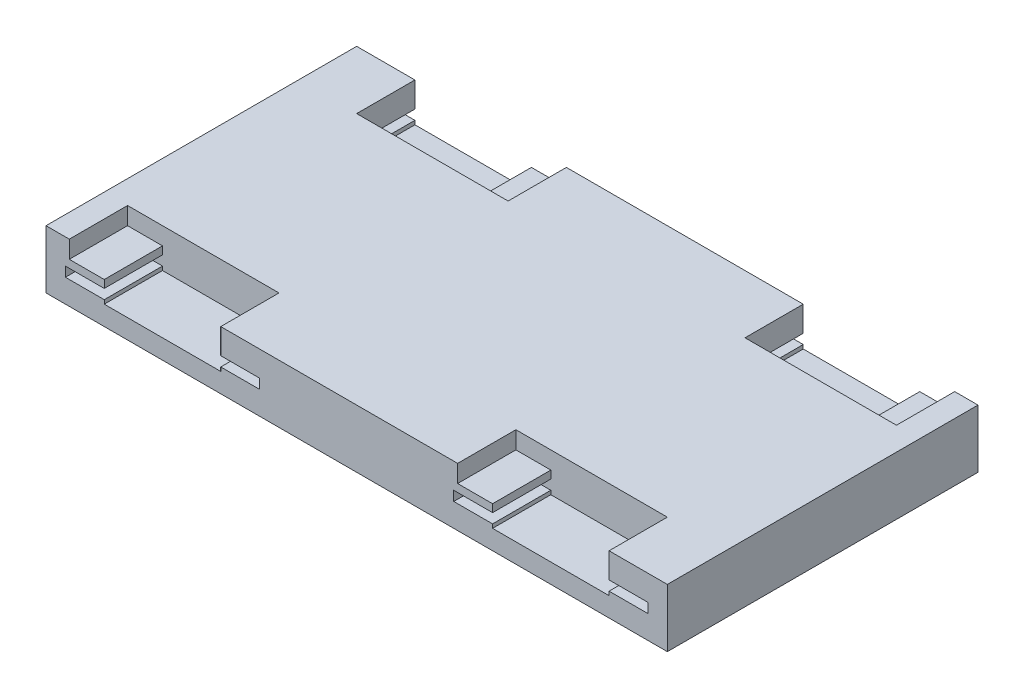
SolidWorks part; units mm, degrees
ref_plane "Front Plane" through (0, 0, 0) normal (0, 0, 1) x (1, 0, 0)
ref_plane "Top Plane" through (0, 0, 0) normal (0, 1, 0) x (1, 0, 0)
ref_plane "Right Plane" through (0, 0, 0) normal (1, 0, 0) x (0, 0, -1)
sketch "Sketch1" plane through (0, 0, 0) normal (0, 1, 0) x (1, 0, 0)
  line L1 (-160, 80) -> (160, 80)
  line L2 (-160, 80) -> (-160, -80)
  line L3 (-160, -80) -> (160, -80)
  line L4 (160, 80) -> (160, -80)
  line L5 (-160, 80) -> (160, -80) construction
  line L6 (-160, -80) -> (160, 80) construction
  point P0 (0, 0)
  dimension "D1" = 320
  dimension "D2" = 160
extrude "Boss-Extrude1" add sketch "Sketch1" along normal blind 20
sketch "Sketch2" plane through (0, 20, 0) normal (0, 1, 0) x (1, 0, 0)
  line L0 (-160, -80) -> (160, -80) construction
  line L1 (-130, -80) -> (-70, -80)
  line L2 (-130, -80) -> (-130, -50)
  line L3 (-130, -50) -> (-70, -50)
  line L4 (-70, -80) -> (-70, -50)
  line L5 (-160, 80) -> (-160, -80) construction
  dimension "D1" = 60
  dimension "D2" = 30
  dimension "D3" = 30
extrude "Cut-Extrude1" cut sketch "Sketch2" against normal blind 28
sketch "Sketch3" plane through (0, 0, 80) normal (0, 0, 1) x (1, 0, 0)
  line L0 (-130, 0) -> (-130, 20) construction
  line L1 (-130, 7) -> (-150, 7)
  line L2 (-130, 7) -> (-130, 2)
  line L3 (-130, 2) -> (-150, 2)
  line L4 (-150, 7) -> (-150, 2)
  line L5 (-160, 0) -> (-130, 0) construction
  line L6 (-70, 0) -> (-70, 20) construction
  line L7 (-70, 7) -> (-50, 7)
  line L8 (-70, 7) -> (-70, 2)
  line L9 (-70, 2) -> (-50, 2)
  line L10 (-50, 7) -> (-50, 2)
  line L11 (88, 0) -> (-88, 0) construction
  dimension "D1" = 2
  dimension "D2" = 5
  dimension "D3" = 20
  dimension "D4" = 20
  dimension "D5" = 5
  dimension "D6" = 2
extrude "Cut-Extrude3" cut sketch "Sketch3" against normal blind 30
mirror "Mirror2" about plane through (0, 0, 0) normal (1, 0, 0) of "Cut-Extrude1", "Cut-Extrude3"
mirror "Mirror3" about plane through (0, 0, 0) normal (0, 0, 1) of "Mirror2", "Cut-Extrude1", "Cut-Extrude3"
sketch "Sketch5" plane through (0, 0, 80) normal (0, 0, 1) x (1, 0, 0)
  line L0 (-130, 7) -> (-130, 20) construction
  line L1 (-130, 11) -> (-148, 11)
  line L2 (-130, 11) -> (-130, 20)
  line L3 (-130, 20) -> (-148, 20)
  line L4 (-148, 11) -> (-148, 20)
  line L5 (-160, 20) -> (-130, 20) construction
  line L6 (-130, 7) -> (-150, 7) construction
  dimension "D1" = 4
  dimension "D2" = 18
extrude "Cut-Extrude4" cut sketch "Sketch5" against normal blind 30
sketch "Sketch6" plane through (0, 0, 80) normal (0, 0, 1) x (1, 0, 0)
  line L0 (70, 7) -> (70, 20) construction
  line L1 (70, 11) -> (52, 11)
  line L2 (70, 11) -> (70, 20)
  line L3 (70, 20) -> (52, 20)
  line L4 (52, 11) -> (52, 20)
  line L5 (50, 7) -> (70, 7) construction
  dimension "D1" = 18
  dimension "D2" = 4
extrude "Cut-Extrude5" cut sketch "Sketch6" against normal blind 30
sketch "Sketch8" plane through (0, 0, -80) normal (0, 0, -1) x (-1, 0, 0)
  line L0 (-130, 7) -> (-130, 20) construction
  line L1 (-130, 11) -> (-148, 11)
  line L2 (-130, 11) -> (-130, 20)
  line L3 (-130, 20) -> (-148, 20)
  line L4 (-148, 11) -> (-148, 20)
  line L5 (-160, 20) -> (-130, 20) construction
  line L6 (-130, 7) -> (-150, 7) construction
  dimension "D1" = 18
  dimension "D2" = 4
extrude "Cut-Extrude6" cut sketch "Sketch8" against normal blind 30
sketch "Sketch9" plane through (0, 0, -80) normal (0, 0, -1) x (-1, 0, 0)
  line L0 (70, 20) -> (70, 7) construction
  line L1 (70, 11) -> (52, 11)
  line L2 (70, 11) -> (70, 20)
  line L3 (70, 20) -> (52, 20)
  line L4 (52, 11) -> (52, 20)
  line L5 (-70, 20) -> (70, 20) construction
  line L6 (50, 7) -> (70, 7) construction
  dimension "D1" = 18
  dimension "D2" = 4
extrude "Cut-Extrude7" cut sketch "Sketch9" against normal blind 30
sketch "Sketch10" plane through (0, 0, 0) normal (0, -1, 0) x (1, 0, 0)
  line L1 (-160, 80) -> (160, 80)
  line L2 (-160, 80) -> (-160, -80)
  line L3 (-160, -80) -> (160, -80)
  line L4 (160, 80) -> (160, -80)
extrude "Boss-Extrude2" add sketch "Sketch10" along normal blind 10
